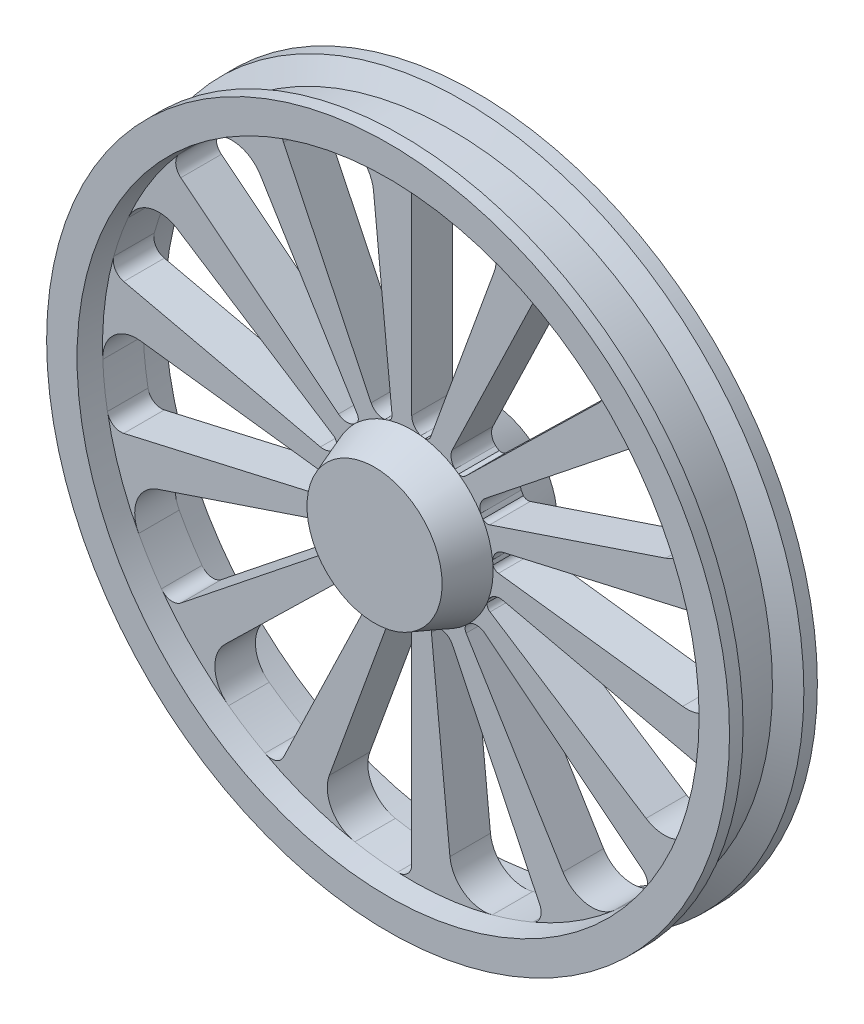
SolidWorks part; units mm, degrees
material "1060 Alloy"
ref_plane "Front Plane" through (0, 0, 0) normal (0, 0, 1) x (1, 0, 0)
ref_plane "Top Plane" through (0, 0, 0) normal (0, 1, 0) x (1, 0, 0)
ref_plane "Right Plane" through (0, 0, 0) normal (1, 0, 0) x (0, 0, -1)
sketch "Sketch1" plane through (0, 0, 0) normal (1, 0, 0) x (0, 0, -1)
  line L0 (0, -475.2546) -> (0, 475.2546) construction
  line L1 (-374.6363, 0) -> (374.6363, 0) construction
  line L2 (-85, 0) -> (-85, 100)
  line L3 (-85, 100) -> (-30, 120.4073)
  line L4 (-30, 120.4073) -> (-30, 457.5)
  line L5 (85, 0) -> (85, 100)
  line L6 (85, 100) -> (30, 120.4073)
  line L7 (30, 120.4073) -> (30, 457.5)
  line L8 (-30, 457.5) -> (-65, 460.2546)
  line L9 (-65, 460.2546) -> (-65, 505.2546)
  line L10 (-65, 505.2546) -> (-45, 505.2546)
  line L11 (-45, 505.2546) -> (-28.5083, 475.2546)
  line L12 (-28.5083, 475.2546) -> (28.5083, 475.2546)
  line L13 (28.5083, 475.2546) -> (45, 505.2546)
  line L14 (45, 505.2546) -> (65, 505.2546)
  line L15 (65, 505.2546) -> (65, 460.2546)
  line L16 (65, 460.2546) -> (30, 457.5)
  line L17 (-85, 0) -> (85, 0)
  point P3 (0, 0)
  point P4 (0, 0)
  point P8 (0, 0)
  point P14 (0.1567, 475.2546)
  point P25 (0, 0)
  dimension "D1" = 100
  dimension "D2" = 170
  dimension "D3" = 60
  dimension "D4" = 457.5
  dimension "D5" = 30
  dimension "D6" = 20
  dimension "D7" = 45
  dimension "D8" = 130
  dimension "D9" = 57.0165
  dimension "D10" = 110.357
revolve "Revolve1" add sketch "Sketch1" angle 360 about L1
sketch "Sketch2" plane through (0, 0, 30) normal (0, 0, 1) x (1, 0, 0)
  line L0 (0, -437.0426) -> (0, -120)
  line L1 (-505.2546, 0) -> (505.2546, 0) construction
  line L2 (27.9684, 125.2464) -> (121.945, 383.4451)
  line L3 (0, 0) -> (0, 437.0426) construction
  line L4 (189.6257, 393.7618) -> (60.1207, 124.8419)
  line L5 (79.541, 100.7081) -> (276.2392, 292.5622)
  line L6 (0, 437.0426) -> (0, 138.5641)
  line L7 (341.6937, 272.4916) -> (108.3337, 86.3933)
  line L8 (115.3596, 56.2233) -> (375.8209, 143.7337)
  line L9 (426.085, 97.2511) -> (135.09, 30.8334)
  line L10 (128.3298, 0.6028) -> (400.9667, -33.563)
  line L11 (426.085, -97.2511) -> (135.09, -30.8334)
  line L12 (115.8827, -55.1371) -> (346.696, -204.2121)
  line L13 (341.6937, -272.4916) -> (108.3337, -86.3933)
  line L14 (80.4836, -99.9564) -> (223.758, -334.4146)
  line L15 (189.6257, -393.7618) -> (60.1207, -124.8419)
  line L16 (29.1438, -124.9781) -> (56.502, -398.3821)
  line L17 (0, -437.0426) -> (0, -138.5641)
  line L18 (-27.9684, -125.2464) -> (-121.945, -383.4451)
  line L19 (-189.6257, -393.7618) -> (-60.1207, -124.8419)
  line L20 (-79.541, -100.7081) -> (-276.2392, -292.5622)
  line L21 (-341.6937, -272.4916) -> (-108.3337, -86.3933)
  line L22 (-115.3596, -56.2233) -> (-375.8209, -143.7337)
  line L23 (-426.085, -97.2511) -> (-135.09, -30.8334)
  line L24 (-128.3298, -0.6028) -> (-400.9667, 33.563)
  line L25 (-426.085, 97.2511) -> (-135.09, 30.8334)
  line L26 (-115.8827, 55.1371) -> (-346.696, 204.2121)
  line L27 (-341.6937, 272.4916) -> (-108.3337, 86.3933)
  line L28 (-80.4836, 99.9564) -> (-223.758, 334.4146)
  line L29 (-189.6257, 393.7618) -> (-60.1207, 124.8419)
  line L30 (-29.1438, 124.9781) -> (-56.502, 398.3821)
  line L31 (0, 0) -> (17.1429, 118.7692) construction
  line L32 (0, 0) -> (66.9772, 99.5693) construction
  circle A0 centre (0, 0) radius 505.2546 construction
  circle A3 centre (0, 0) radius 120
  arc A4 (0, 138.5641) -> (17.1429, 118.7692) centre (20, 138.5641) ccw
  arc A5 (27.9684, 125.2464) -> (17.1429, 118.7692) centre (18.5714, 128.6666) cw
  circle A6 centre (0, 0) radius 457.5
  arc A7 (20.9143, 457.0217) -> (0, 437.0426) centre (20, 437.0426) ccw
  arc A8 (84.1579, 449.6929) -> (121.945, 383.4451) centre (74.9604, 400.5461) cw
  arc A9 (270.9381, 368.6445) -> (276.2392, 292.5622) centre (241.3274, 328.3555) cw
  arc A10 (217.1374, 402.688) -> (189.6257, 393.7618) centre (207.6451, 385.0841) ccw
  arc A11 (60.1207, 124.8419) -> (66.9772, 99.5693) centre (78.1401, 116.1642) ccw
  arc A12 (79.541, 100.7081) -> (66.9772, 99.5693) centre (72.5586, 107.8668) cw
  arc A13 (404.0557, 214.5816) -> (375.8209, 143.7337) centre (359.8966, 191.1301) cw
  arc A14 (370.3538, 268.5969) -> (341.6937, 272.4916) centre (354.1635, 256.855) ccw
  arc A15 (108.3337, 86.3933) -> (103.5459, 60.6486) centre (120.8035, 70.7567) ccw
  arc A16 (115.3596, 56.2233) -> (103.5459, 60.6486) centre (112.1747, 65.7026) cw
  arc A17 (457.145, 18.0181) -> (400.9667, -33.563) centre (407.1838, 16.049) cw
  arc A18 (450.2171, 81.307) -> (426.085, 97.2511) centre (430.5355, 77.7526) ccw
  arc A19 (135.09, 30.8334) -> (119.6061, 9.7156) centre (139.5404, 11.3348) ccw
  arc A20 (128.3298, 0.6028) -> (119.6061, 9.7156) centre (129.5732, 10.5252) cw
  arc A21 (419.6912, -182.114) -> (346.696, -204.2121) centre (373.8233, -162.2108) cw
  arc A22 (440.9094, -122.0868) -> (426.085, -97.2511) centre (421.6346, -116.7497) ccw
  arc A23 (135.09, -30.8334) -> (111.9768, -43.1417) centre (130.6396, -50.332) ccw
  arc A24 (115.8827, -55.1371) -> (111.9768, -43.1417) centre (121.3082, -46.7368) cw
  arc A25 (299.1124, -346.1763) -> (223.758, -334.4146) centre (266.4225, -308.3428) cw
  arc A26 (344.2741, -301.2998) -> (341.6937, -272.4916) centre (329.2239, -288.1282) ccw
  arc A27 (108.3337, -86.3933) -> (82.1691, -87.4542) centre (95.864, -102.0299) ccw
  arc A28 (80.4836, -99.9564) -> (82.1691, -87.4542) centre (89.0165, -94.7421) cw
  arc A29 (119.2907, -441.6741) -> (56.502, -398.3821) centre (106.2535, -393.4037) cw
  arc A30 (179.4512, -420.8367) -> (189.6257, -393.7618) centre (171.6063, -402.4395) ccw
  arc A31 (60.1207, -124.8419) -> (36.0868, -114.4454) centre (42.1013, -133.5196) ccw
  arc A32 (29.1438, -124.9781) -> (36.0868, -114.4454) centre (39.0941, -123.9825) cw
  arc A33 (-84.1579, -449.6929) -> (-121.945, -383.4451) centre (-74.9604, -400.5461) cw
  arc A34 (-20.9143, -457.0217) -> (0, -437.0426) centre (-20, -437.0426) ccw
  arc A35 (0, -138.5641) -> (-17.1429, -118.7692) centre (-20, -138.5641) ccw
  arc A36 (-27.9684, -125.2464) -> (-17.1429, -118.7692) centre (-18.5714, -128.6666) cw
  arc A37 (-270.9381, -368.6445) -> (-276.2392, -292.5622) centre (-241.3274, -328.3555) cw
  arc A38 (-217.1374, -402.688) -> (-189.6257, -393.7618) centre (-207.6451, -385.0841) ccw
  arc A39 (-60.1207, -124.8419) -> (-66.9772, -99.5693) centre (-78.1401, -116.1642) ccw
  arc A40 (-79.541, -100.7081) -> (-66.9772, -99.5693) centre (-72.5586, -107.8668) cw
  arc A41 (-404.0557, -214.5816) -> (-375.8209, -143.7337) centre (-359.8966, -191.1301) cw
  arc A42 (-370.3538, -268.5969) -> (-341.6937, -272.4916) centre (-354.1635, -256.855) ccw
  arc A43 (-108.3337, -86.3933) -> (-103.5459, -60.6486) centre (-120.8035, -70.7567) ccw
  arc A44 (-115.3596, -56.2233) -> (-103.5459, -60.6486) centre (-112.1747, -65.7026) cw
  arc A45 (-457.145, -18.0181) -> (-400.9667, 33.563) centre (-407.1838, -16.049) cw
  arc A46 (-450.2171, -81.307) -> (-426.085, -97.2511) centre (-430.5355, -77.7526) ccw
  arc A47 (-135.09, -30.8334) -> (-119.6061, -9.7156) centre (-139.5404, -11.3348) ccw
  arc A48 (-128.3298, -0.6028) -> (-119.6061, -9.7156) centre (-129.5732, -10.5252) cw
  arc A49 (-419.6912, 182.114) -> (-346.696, 204.2121) centre (-373.8233, 162.2108) cw
  arc A50 (-440.9094, 122.0868) -> (-426.085, 97.2511) centre (-421.6346, 116.7497) ccw
  arc A51 (-135.09, 30.8334) -> (-111.9768, 43.1417) centre (-130.6396, 50.332) ccw
  arc A52 (-115.8827, 55.1371) -> (-111.9768, 43.1417) centre (-121.3082, 46.7368) cw
  arc A53 (-299.1124, 346.1763) -> (-223.758, 334.4146) centre (-266.4225, 308.3428) cw
  arc A54 (-344.2741, 301.2998) -> (-341.6937, 272.4916) centre (-329.2239, 288.1282) ccw
  arc A55 (-108.3337, 86.3933) -> (-82.1691, 87.4542) centre (-95.864, 102.0299) ccw
  arc A56 (-80.4836, 99.9564) -> (-82.1691, 87.4542) centre (-89.0165, 94.7421) cw
  arc A57 (-119.2907, 441.6741) -> (-56.502, 398.3821) centre (-106.2535, 393.4037) cw
  arc A58 (-179.4512, 420.8367) -> (-189.6257, 393.7618) centre (-171.6063, 402.4395) ccw
  arc A59 (-60.1207, 124.8419) -> (-36.0868, 114.4454) centre (-42.1013, 133.5196) ccw
  arc A60 (-29.1438, 124.9781) -> (-36.0868, 114.4454) centre (-39.0941, 123.9825) cw
  point P7 (0, 0)
  point P13 (0, 0)
  point P16 (0, 0)
  point P25 (0, 0)
  circle M3 centre (0, 0) radius 120.4073
  dimension "D1" = 240
  dimension "D2" = 20
  dimension "D3" = 915
  dimension "D4" = 20
  dimension "D5" = 50
  dimension "D6" = 10
  dimension "D7" = 20
  dimension "D8" = 14
  dimension "D9" = 25.714
extrude "Cut-Extrude1" cut sketch "Sketch2" against normal blind 265 contours A8 A6 A7 L6 A4 A5 L2 M3 | A12 L5 A9 A6 A10 L4 A11 M3 | A16 L8 A13 A6 A14 L7 A15 M3 | A20 L10 A17 A6 A18 L9 A19 M3 | A24 L12 A21 A6 A22 L11 A23 M3 | A28 L14 A25 A6 A26 L13 A27 M3 | A32 L16 A29 A6 A30 L15 A31 M3 | A36 L18 A33 A6 A34 L0 A35 M3 | A40 L20 A37 A6 A38 L19 A39 M3 | A44 L22 A41 A6 A42 L21 A43 M3 | A48 L24 A45 A6 A46 L23 A47 M3 | A52 L26 A49 A6 A50 L25 A51 M3 | A56 L28 A53 A6 A54 L27 A55 M3 | A60 L30 A57 A6 A58 L29 A59 M3
